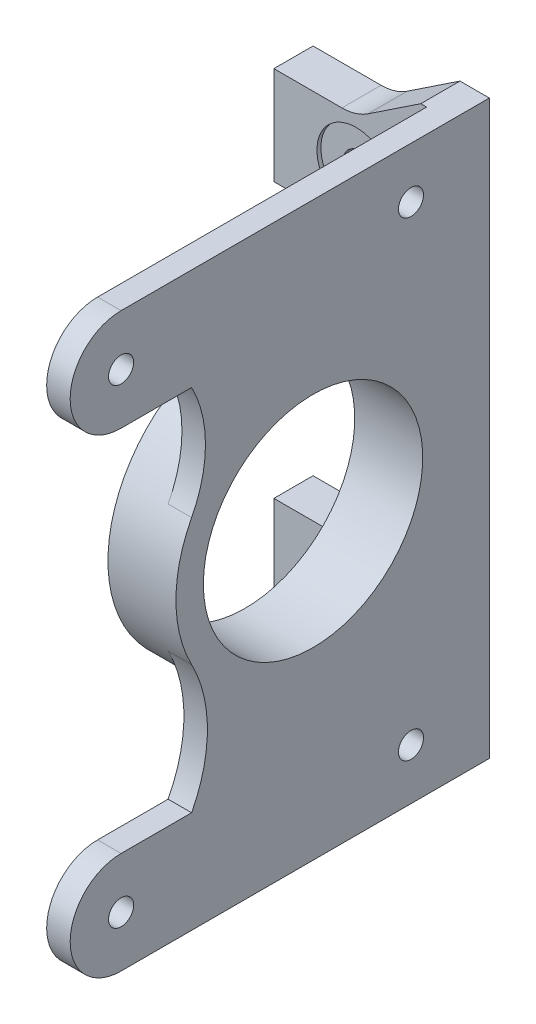
SolidWorks part; units mm, degrees
ref_plane "前视基准面" through (0, 0, 0) normal (0, 0, 1) x (1, 0, 0)
ref_plane "上视基准面" through (0, 0, 0) normal (0, 1, 0) x (1, 0, 0)
ref_plane "右视基准面" through (0, 0, 0) normal (1, 0, 0) x (0, 0, -1)
sketch "草图2" plane through (0, 0, 0) normal (0, 0, 1) x (1, 0, 0)
  line L0 (-14.7736, 24.3382) -> (-14.7736, -35.6618)
  line L1 (-14.7736, -35.6618) -> (30.2264, -35.6618)
  line L2 (7.7264, -35.6618) -> (7.7264, -23.1618)
  line L3 (21.55, -23.1618) -> (-6.0971, -23.1618)
  line L4 (-6.0971, -23.1618) -> (-6.0971, 11.8382)
  line L5 (-6.0971, 11.8382) -> (21.55, 11.8382)
  line L6 (7.7264, 11.8382) -> (7.7264, 24.3382)
  line L7 (30.2264, 24.3382) -> (-14.7736, 24.3382)
  line L8 (7.7264, 28.8603) -> (7.7264, -39.8897) construction
  line L9 (21.55, -23.1618) -> (21.55, 11.8382)
  line L10 (30.2264, 24.3382) -> (30.2264, -35.6618)
  line L11 (-18.1559, -5.6618) -> (33.2411, -5.6618) construction
  point P16 (-6.0971, -5.6618)
  point P17 (-14.7736, -5.6618)
  dimension "D1" = 45
  dimension "D2" = 35
  dimension "D3" = 60
extrude "凸台-拉伸2" add sketch "草图2" along normal blind 5 contours L6 L7 L0 L1 L2 L3 L4 L5 | L10 L7 L6 L5 L9 L3 L2 L1
sketch "草图4" plane through (0, 0, 5) normal (0, 0, 1) x (1, 0, 0)
  line L0 (-18.165, -5.6618) -> (33.9165, -5.6618) construction
  line L1 (-14.7736, 24.3382) -> (-14.7736, -35.6618) construction
  line L2 (-14.7736, -23.1618) -> (-6.0971, -23.1618)
  line L3 (-14.7736, -23.1618) -> (-14.7736, 11.8382)
  line L4 (-14.7736, 11.8382) -> (-6.0971, 11.8382)
  line L5 (-6.0971, -23.1618) -> (-6.0971, 11.8382)
  line L6 (-6.0971, -23.1618) -> (-6.0971, 11.8382) construction
  line L7 (7.7264, -39.813) -> (7.7264, 28.1228) construction
  line L8 (30.2264, 11.8382) -> (21.55, 11.8382)
  line L9 (21.55, -23.1618) -> (21.55, 11.8382)
  line L10 (30.2264, -23.1618) -> (21.55, -23.1618)
  line L11 (30.2264, -23.1618) -> (30.2264, 11.8382)
  point P17 (-14.7736, -5.6618)
  dimension "D1" = 35
extrude "凸台-拉伸15" add sketch "草图4" along normal blind 35
sketch "草图5" plane through (-14.7736, 0, 0) normal (-1, 0, 0) x (0, 0, 1)
  line L0 (0, -5.6618) -> (40, -5.6618)
  line L1 (0, 24.3382) -> (0, -35.6618) construction
  line L2 (40, 11.8382) -> (40, -23.1618) construction
  line L3 (22.5, 11.8382) -> (40, 11.8382)
  line L4 (40, 11.8382) -> (40, -23.1618)
  line L5 (40, -23.1618) -> (22.5, -23.1618)
  circle A0 centre (22.5, -5.6618) radius 17.5
  line M5 (5, -23.1618) -> (40, -23.1618)
  line M6 (40, -23.1618) -> (40, 11.8382)
  line M7 (40, 11.8382) -> (5, 11.8382)
  dimension "D1" = 35
extrude "切除-拉伸1" cut sketch "草图5" against normal blind 45 contours A0 M5 M6 | A0 M6 M7
sketch "草图6" plane through (-14.7736, 0, 0) normal (-1, 0, 0) x (0, 0, 1)
  circle A0 centre (22.5, -5.6618) radius 14
  dimension "D1" = 28
extrude "切除-拉伸2" cut sketch "草图6" against normal blind 45
fillet "圆角1" radius 5 4 edges at (-6.0971, 11.8382, 2.5) (21.55, 11.8382, 2.5) (-6.0971, -23.1618, 2.5) (21.55, -23.1618, 2.5)
sketch "草图7" plane through (-6.0971, 0, 0) normal (1, 0, 0) x (0, 0, -1)
  circle A0 centre (-22.5, -5.6618) radius 15
  circle A1 centre (-22.5, -5.6618) radius 13
extrude "凸台-拉伸16" add sketch "草图7" against normal blind 1
sketch "草图8" plane through (21.55, 0, 0) normal (-1, 0, 0) x (0, 0, 1)
  circle A0 centre (22.5, -5.6618) radius 15
  circle A1 centre (22.5, -5.6618) radius 10
sketch "草图9" plane through (0, 0, 5) normal (0, 0, 1) x (1, 0, 0)
  line L0 (7.7264, 24.3382) -> (7.7264, -35.6618)
  line L13 (30.2264, 24.3382) -> (-14.7736, 24.3382) construction
  line L14 (-14.7736, -35.6618) -> (30.2264, -35.6618) construction
sketch "草图11" plane through (0, 0, 5) normal (0, 0, 1) x (1, 0, 0)
  line L0 (-14.7736, 18.0882) -> (30.2264, 18.0882)
  line L1 (-14.7736, 24.3382) -> (-14.7736, 11.8382) construction
  line L2 (30.2264, 24.3382) -> (30.2264, 11.8382) construction
  line L3 (7.7264, 24.3382) -> (7.7264, -35.6618) construction
  line L4 (30.2264, 24.3382) -> (-14.7736, 24.3382) construction
  line L5 (-14.7736, -35.6618) -> (30.2264, -35.6618) construction
  line L6 (7.7264, -5.6618) -> (45.6912, -5.6618) construction
  line L7 (45.6912, -5.6618) -> (45.6912, 4.9969) construction
  line L10 (-14.7736, -29.4118) -> (30.2264, -29.4118)
  line L11 (-14.7736, -23.1618) -> (-14.7736, -35.6618) construction
  point P4 (-2.7736, 18.0882)
  point P16 (-2.7736, -29.4118)
  point P18 (18.2264, -29.4118)
  point P25 (18.2264, 18.0882)
  dimension "D1" = 12
split "分割1" trim tools "草图9" bodies to split 111 resulting bodies 117 118
delete or keep bodies "实体-删除/保留 2" type delete bodies bodies 117
sketch "草图17" plane through (0, 0, 5) normal (0, 0, 1) x (1, 0, 0)
  line L0 (21.55, -23.1618) -> (30.2264, -23.1618) construction
  line L1 (30.2264, -43.1618) -> (27.2264, -43.1618)
  line L2 (30.2264, -43.1618) -> (30.2264, -30.1618)
  line L3 (30.2264, -30.1618) -> (27.2264, -30.1618)
  line L4 (27.2264, -43.1618) -> (27.2264, -30.1618)
  line L5 (30.2264, 29.8382) -> (27.2264, 29.8382)
  line L6 (30.2264, 29.8382) -> (30.2264, 16.8382)
  line L7 (30.2264, 16.8382) -> (27.2264, 16.8382)
  line L8 (27.2264, 29.8382) -> (27.2264, 16.8382)
  line L9 (30.2264, 24.3382) -> (30.2264, 11.8382) construction
  line L10 (30.2264, 11.8382) -> (21.55, 11.8382) construction
  dimension "D1" = 3
  dimension "D2" = 3
  dimension "D3" = 13
  dimension "D4" = 13
  dimension "D5" = 7
  dimension "D6" = 5
extrude "凸台-拉伸20" add sketch "草图17" along normal blind 42
sketch "草图18" plane through (30.2264, 0, 0) normal (1, 0, 0) x (0, 0, -1)
  line L1 (-47, -43.1618) -> (-47, -30.1618) construction
  line L2 (-47, -30.1618) -> (-47, -43.1618)
  line L3 (-47, 16.8382) -> (-47, 29.8382)
  arc A0 (-47, 29.8382) -> (-47, 16.8382) centre (-47, 23.3382) ccw
  arc A1 (-47, -30.1618) -> (-47, -43.1618) centre (-47, -36.6618) ccw
extrude "凸台-拉伸21" add sketch "草图18" against normal blind 3
sketch "草图19" plane through (30.2264, 0, 0) normal (1, 0, 0) x (0, 0, -1)
  circle A0 centre (-47, 23.3382) radius 1.6
  circle A1 centre (-47, -36.6618) radius 1.6
  circle A2 centre (-10, 23.3382) radius 1.6
  circle A3 centre (-10, -36.6618) radius 1.6
  dimension "D1" = 37
  dimension "D2" = 37
extrude "切除-拉伸3" cut sketch "草图19" against normal blind 3
sketch "草图21" plane through (0, 0, 5) normal (0, 0, 1) x (1, 0, 0)
  line L0 (18.2264, -35.6618) -> (30.2264, -35.6618)
  line L1 (7.7264, -35.6618) -> (27.2264, -35.6618) construction
  line L2 (30.2264, -43.1618) -> (30.2264, -30.1618) construction
  line L3 (30.2264, -35.6618) -> (30.2264, -43.1618)
  line L4 (26.4082, -43.1618) -> (18.2264, -35.6618)
  line L5 (18.2264, 24.3382) -> (30.2264, 24.3382)
  line L6 (27.2264, 24.3382) -> (7.7264, 24.3382) construction
  line L7 (30.2264, 16.8382) -> (30.2264, 29.8382) construction
  line L8 (30.2264, 24.3382) -> (30.2264, 29.8382)
  line L9 (26.4764, 29.8382) -> (18.2264, 24.3382)
  line L10 (27.2264, -43.1618) -> (30.2264, -43.1618) construction
  line L11 (27.2264, -43.1618) -> (30.2264, -43.1618)
  line L12 (27.2264, -43.1618) -> (26.4082, -43.1618)
  line L13 (30.2264, -46.6618) -> (26.4082, -43.1618) construction
  line L14 (30.2264, -43.1618) -> (30.2264, -46.6618) construction
  line L15 (30.2264, 29.8382) -> (26.4764, 29.8382)
  line L16 (30.2264, 29.8382) -> (30.2264, 32.3382) construction
  line L17 (30.2264, 32.3382) -> (26.4764, 29.8382) construction
  dimension "D1" = 11
  dimension "D2" = 12
  dimension "D3" = 12
  dimension "D4" = 8
extrude "凸台-拉伸22" add sketch "草图21" against normal blind 5
sketch "草图24" plane through (30.2264, 0, 0) normal (1, 0, 0) x (0, 0, -1)
  line L10 (-47, -30.1618) -> (-5, -30.1618) construction
  line L11 (-5, 16.8382) -> (-38, 16.8382)
  line L12 (-5, 16.8382) -> (-5, 11.8382)
  line L13 (-5, -30.1618) -> (-38, -30.1618)
  line L14 (-38, 16.8382) -> (-38, 2.4623) construction
  line L15 (-22.5, 11.8382) -> (-5, 11.8382) construction
  line L16 (-22.5, 11.8382) -> (-5, 11.8382)
  line L17 (-22.5, -23.1618) -> (-5, -23.1618) construction
  line L18 (-22.5, -23.1618) -> (-5, -23.1618)
  line L19 (-5, 11.8382) -> (-5, -23.1618) construction
  line L20 (-5, -23.1618) -> (-5, -30.1618)
  line L21 (-38, 2.4623) -> (-38, -13.7858) construction
  line L22 (-38, -13.7858) -> (-38, -30.1618) construction
  arc A2 (-22.5, 11.8382) -> (-22.5, -23.1618) centre (-22.5, -5.6618) ccw construction
  arc A3 (-22.5, 11.8382) -> (-38, 2.4623) centre (-22.5, -5.6618) ccw
  arc A4 (-38, 2.4623) -> (-38, -13.7858) centre (-22.5, -5.6618) ccw construction
  arc A5 (-38, -13.7858) -> (-22.5, -23.1618) centre (-22.5, -5.6618) ccw
  arc A6 (-38, 2.4623) -> (-38, 16.8382) centre (-51.7141, 9.6503) ccw
  arc A7 (-38, -13.7858) -> (-38, -30.1618) centre (-53.622, -21.9738) cw
  dimension "D1" = 33
extrude "凸台-拉伸25" add sketch "草图24" against normal blind 3
hole_wizard "打孔尺寸(%根据六角头螺)栓 全螺纹的类型1" positions "3D草图2" profile "草图31" counterbore size "M4" standard "GB"
sketch3d "3D草图2"
  point P0 (18.2264, 18.0882, 5)
  point P3 (18.2264, -29.4118, 5)
sketch "草图31" plane through (18.2264, 18.0882, 5) normal (1, 0, 0) x (0, -1, 0)
  line L0 (0, 0) -> (0, 6.2919)
  line L1 (0, 6.2919) -> (2.15, 5)
  line L2 (2.15, 5) -> (2.15, 0.5)
  line L3 (2.15, 0.5) -> (5, 0.5)
  line L4 (5, 0.5) -> (5, 0)
  line L5 (5, 0) -> (0, 0)
  line L10 (0, 6.2919) -> (-2.15, 5) construction
  line L11 (0, -6.35) -> (0, 107.95) construction
  dimension "孔直径" = 4.3
  dimension "孔深度" = 5
  dimension "柱形沉头孔直径" = 10
  dimension "柱形沉头孔深度" = 0.5
  dimension "导头角度" = 118
fillet "圆角2" radius 6 2 edges at (18.2264, -35.6618, 2.5) (18.2264, 24.3382, 2.5)
